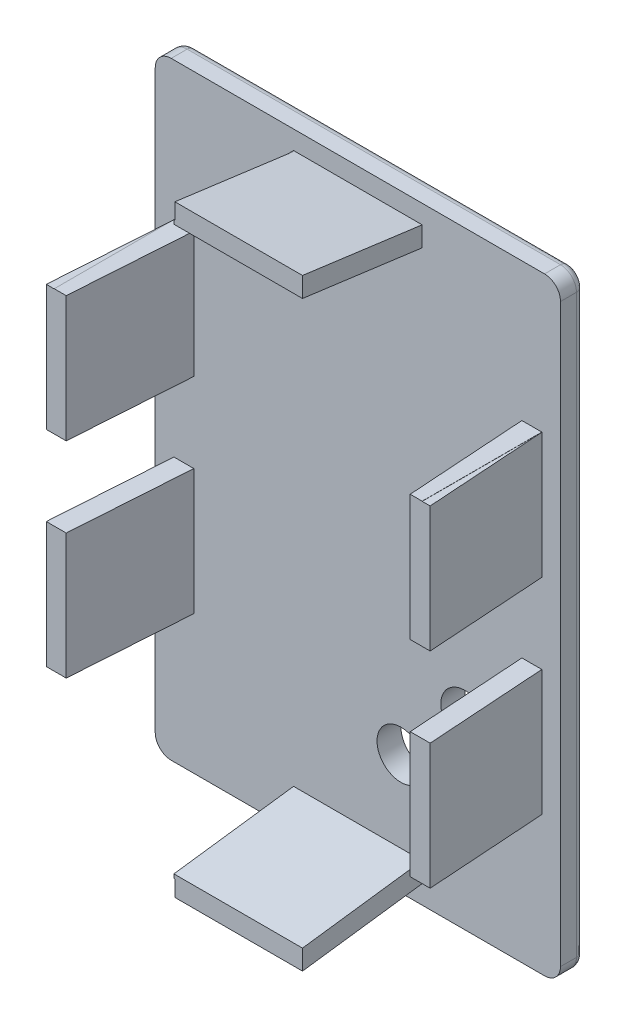
SolidWorks part; units mm, degrees
material "PLA"
ref_plane "Alzado" through (0, 0, 0) normal (0, 0, 1) x (1, 0, 0)
ref_plane "Planta" through (0, 0, 0) normal (0, 1, 0) x (1, 0, 0)
ref_plane "Vista lateral" through (0, 0, 0) normal (1, 0, 0) x (0, 0, -1)
sketch "Croquis1" plane through (0, 0, 0) normal (0, 0, 1) x (1, 0, 0)
  line L1 (25.4, 38.1) -> (-25.4, 38.1)
  line L2 (25.4, 38.1) -> (25.4, -38.1)
  line L3 (25.4, -38.1) -> (-25.4, -38.1)
  line L4 (-25.4, 38.1) -> (-25.4, -38.1)
  line L5 (25.4, 38.1) -> (-25.4, -38.1) construction
  line L6 (25.4, -38.1) -> (-25.4, 38.1) construction
  point P0 (0, 0)
  dimension "D1" = 76.2
  dimension "D2" = 50.8
extrude "Saliente-Extruir1" add sketch "Croquis1" along normal blind 18
sketch "Croquis2" plane through (0, 0, 18) normal (0, 0, 1) x (1, 0, 0)
  line L0 (25.4, 38.1) -> (-25.4, 38.1) construction
  line L1 (-23.06, 35.76) -> (23.06, 35.76)
  line L2 (-23.06, 35.76) -> (-23.06, -35.76)
  line L3 (-23.06, -35.76) -> (23.06, -35.76)
  line L4 (23.06, 35.76) -> (23.06, -35.76)
  line L5 (-25.4, -38.1) -> (25.4, -38.1) construction
  line L6 (-25.4, 38.1) -> (-25.4, -38.1) construction
  line L7 (25.4, -38.1) -> (25.4, 38.1) construction
  line L9 (-25.4, 38.1) -> (25.4, 38.1)
  line L10 (-25.4, 38.1) -> (-25.4, -38.1)
  line L11 (-25.4, -38.1) -> (25.4, -38.1)
  line L12 (25.4, 38.1) -> (25.4, -38.1)
  line L13 (-19.4, 32.1) -> (19.4, 32.1)
  line L14 (-19.4, 32.1) -> (-19.4, -32.1)
  line L15 (-19.4, -32.1) -> (19.4, -32.1)
  line L16 (19.4, 32.1) -> (19.4, -32.1)
  line M9 (-25.4, 38.1) -> (-25.4, -38.1)
  line M10 (-25.4, -38.1) -> (25.4, -38.1)
  line M11 (25.4, -38.1) -> (25.4, 38.1)
  line M12 (25.4, 38.1) -> (-25.4, 38.1)
  dimension "D1" = 2.34
  dimension "D2" = 2.34
  dimension "D3" = 2.34
  dimension "D4" = 2.34
  dimension "D5" = 6
  dimension "D6" = 6
  dimension "D7" = 6
  dimension "D8" = 6
extrude "Cortar-Extruir1" cut sketch "Croquis2" against normal blind 15 contours L1 L4 L3 L2 M12 M9 M10 M11 | L16 L13 L14 L15
sketch "Croquis3" plane through (0, 0, 18) normal (0, 0, 1) x (1, 0, 0)
  line L0 (-23.06, 35.76) -> (-23.06, -35.76) construction
  line L1 (-23.06, 22.1) -> (-19.4, 22.1)
  line L2 (-23.06, 22.1) -> (-23.06, -22.1)
  line L3 (-23.06, -22.1) -> (-19.4, -22.1)
  line L4 (-19.4, 22.1) -> (-19.4, -22.1)
  line L5 (-19.4, 32.1) -> (-19.4, -32.1) construction
  line L6 (-19.4, -32.1) -> (19.4, -32.1) construction
  line L7 (-9.4, -32.1) -> (9.3837, -32.1)
  line L8 (-9.4, -32.1) -> (-9.4, -35.76)
  line L9 (-9.4, -35.76) -> (9.3837, -35.76)
  line L10 (9.3837, -32.1) -> (9.3837, -35.76)
  line L11 (-23.06, -35.76) -> (23.06, -35.76) construction
  line L12 (19.4, 32.1) -> (19.4, -32.1) construction
  line L13 (19.4, -22.1) -> (23.06, -22.1)
  line L14 (19.4, -22.1) -> (19.4, 22.1)
  line L15 (19.4, 22.1) -> (23.06, 22.1)
  line L16 (23.06, -22.1) -> (23.06, 22.1)
  line L17 (23.06, 35.76) -> (23.06, -35.76) construction
  line L18 (-23.06, 35.76) -> (23.06, 35.76) construction
  line L19 (-9.4, 35.76) -> (9.4, 35.76)
  line L20 (-9.4, 35.76) -> (-9.4, 32.1)
  line L21 (-9.4, 32.1) -> (9.4, 32.1)
  line L22 (9.4, 35.76) -> (9.4, 32.1)
  line L23 (-19.4, 32.1) -> (19.4, 32.1) construction
  line L24 (-19.4, 32.1) -> (-19.4, -32.1) construction
  line L25 (19.4, 32.1) -> (19.4, -32.1) construction
  dimension "D1" = 10
  dimension "D2" = 10
  dimension "D3" = 10
  dimension "D4" = 10
  dimension "D5" = 10
  dimension "D6" = 10
  dimension "D7" = 10
extrude "Cortar-Extruir2" [suppressed] cut sketch "Croquis3" against normal blind 7
fillet "Redondeo1" [suppressed] radius 2
fillet "Redondeo2" [suppressed] radius 1
sketch "Croquis5" [suppressed] plane through (0, -38.1, 0) normal (0, -1, 0) x (1, 0, 0)
  line L0 (-23.4, 3) -> (23.4, 3) construction
  line L1 (-3, 3) -> (3, 3)
  line L2 (-3, 3) -> (-3, 1.5)
  line L3 (-3, 1.5) -> (3, 1.5)
  line L4 (3, 3) -> (3, 1.5)
  line L5 (0, 1) -> (0, 3) construction
  line L6 (-23.4, 1) -> (23.4, 1) construction
  dimension "D1" = 3
  dimension "D2" = 3
  dimension "D3" = 1.5
extrude "Cortar-Extruir4" [suppressed] cut sketch "Croquis5" against normal blind 6
sketch "Croquis6" plane through (0, 0, 18) normal (0, 0, 1) x (1, 0, 0)
  line L0 (-23.06, 35.76) -> (-8.06, 35.76)
  line L1 (-23.06, 35.76) -> (23.06, 35.76) construction
  line L2 (-8.06, 35.76) -> (-8.06, 32.1)
  line L3 (-19.4, 32.1) -> (19.4, 32.1) construction
  line L4 (-8.06, 32.1) -> (-19.4, 32.1)
  line L5 (-19.4, 32.1) -> (-19.4, 20.76)
  line L6 (-19.4, 32.1) -> (-19.4, -32.1) construction
  line L7 (-19.4, 20.76) -> (-23.06, 20.76)
  line L8 (-23.06, 35.76) -> (-23.06, -35.76) construction
  line L9 (-23.06, 20.76) -> (-23.06, 35.76)
  line L10 (23.06, 35.76) -> (8.06, 35.76)
  line L11 (-23.06, 35.76) -> (23.06, 35.76) construction
  line L12 (8.06, 35.76) -> (8.06, 32.1)
  line L13 (8.06, 32.1) -> (19.4, 32.1)
  line L14 (19.4, 32.1) -> (19.4, -32.1) construction
  line L15 (19.4, 32.1) -> (19.4, -32.1) construction
  line L16 (19.4, 32.1) -> (19.4, 20.76)
  line L17 (19.4, 20.76) -> (23.06, 20.76)
  line L18 (23.06, 35.76) -> (23.06, -35.76) construction
  line L19 (23.06, 20.76) -> (23.06, 35.76)
  line L20 (-23.06, -35.76) -> (-23.06, -20.76)
  line L21 (-23.06, 35.76) -> (-23.06, -35.76) construction
  line L22 (-23.06, -20.76) -> (-19.4, -20.76)
  line L23 (-19.4, 32.1) -> (-19.4, -32.1) construction
  line L24 (-19.4, -20.76) -> (-19.4, -32.1)
  line L25 (-19.4, -32.1) -> (-8.06, -32.1)
  line L26 (-19.4, -32.1) -> (19.4, -32.1) construction
  line L27 (-8.06, -32.1) -> (-8.06, -35.76)
  line L28 (-23.06, -35.76) -> (23.06, -35.76) construction
  line L29 (-8.06, -35.76) -> (-23.06, -35.76)
  line L30 (23.06, -35.76) -> (8.06, -35.76)
  line L31 (-23.06, -35.76) -> (23.06, -35.76) construction
  line L32 (8.06, -35.76) -> (8.06, -32.1)
  line L33 (-19.4, -32.1) -> (19.4, -32.1) construction
  line L34 (8.06, -32.1) -> (19.4, -32.1)
  line L35 (19.4, -32.1) -> (19.4, -20.76)
  line L36 (19.4, -20.76) -> (23.06, -20.76)
  line L37 (23.06, 35.76) -> (23.06, -35.76) construction
  line L38 (23.06, -20.76) -> (23.06, -35.76)
  dimension "D1" = 15
  dimension "D2" = 15
  dimension "D3" = 15
  dimension "D4" = 15
  dimension "D5" = 15
  dimension "D6" = 15
  dimension "D7" = 15
  dimension "D8" = 15
extrude "Cortar-Extruir8" cut sketch "Croquis6" against normal blind 15
sketch "Croquis10" plane through (0, -20.76, 0) normal (0, -1, 0) x (-1, 0, 0)
  line L0 (23.06, -18) -> (24.06, -18)
  line L1 (24.06, -18) -> (23.06, -3)
  line L2 (23.06, -3) -> (23.06, -18)
  line L3 (-23.06, -18) -> (-24.06, -18)
  line L4 (-24.06, -18) -> (-23.06, -3)
  line L5 (-23.06, -3) -> (-23.06, -18)
  dimension "D1" = 1
  dimension "D2" = 1
extrude "Saliente-Extruir3" add sketch "Croquis10" against normal blind 41.5
sketch "Croquis11" plane through (0, -20.76, 0) normal (0, -1, 0) x (1, 0, 0)
  line L0 (-19.4, 18) -> (-21.56, 18)
  line L1 (-19.4, 18) -> (-24.06, 18) construction
  line L2 (-21.56, 18) -> (-20.56, 3)
  line L3 (-19.4, 3) -> (-23.06, 3) construction
  line L4 (-20.56, 3) -> (-19.4, 3)
  line L5 (-19.4, 18) -> (-19.4, 3)
  dimension "D1" = 2.5
  dimension "D2" = 1.16
extrude "Cortar-Extruir9" cut sketch "Croquis11" against normal blind 51.5
sketch "Croquis12" plane through (0, -20.76, 0) normal (0, -1, 0) x (1, 0, 0)
  line L0 (19.4, 18) -> (19.4, 3)
  line L1 (19.4, 3) -> (20.56, 3)
  line L2 (23.06, 3) -> (19.4, 3) construction
  line L3 (20.56, 3) -> (21.56, 18)
  line L4 (24.06, 18) -> (19.4, 18) construction
  line L5 (21.56, 18) -> (19.4, 18)
  dimension "D1" = 2.5
  dimension "D2" = 1.16
extrude "Cortar-Extruir10" cut sketch "Croquis12" against normal blind 51.5
sketch "Croquis13" plane through (8.06, 0, 0) normal (1, 0, 0) x (0, 0, -1)
  line L0 (-18, -35.76) -> (-18, -37.76)
  line L1 (-18, -37.76) -> (-3, -35.76)
  line L2 (-3, -35.76) -> (-18, -35.76)
  line L3 (-18, 35.76) -> (-18, 37.76)
  line L4 (-18, 37.76) -> (-3, 35.76)
  line L5 (-3, 35.76) -> (-18, 35.76)
  dimension "D1" = 2
  dimension "D2" = 2
extrude "Saliente-Extruir4" add sketch "Croquis13" against normal blind 16
sketch "Croquis14" plane through (8.06, 0, 0) normal (1, 0, 0) x (0, 0, -1)
  line L0 (-3, -32.1) -> (-18, -32.1)
  line L1 (-18, -32.1) -> (-18, -35.26)
  line L2 (-18, -32.1) -> (-18, -37.76) construction
  line L3 (-18, -35.26) -> (-3, -33.26)
  line L4 (-3, -32.1) -> (-3, -35.76) construction
  line L5 (-3, -33.26) -> (-3, -32.1)
  line L6 (-18, 32.1) -> (-18, 35.26)
  line L7 (-18, 37.76) -> (-18, 32.1) construction
  line L8 (-18, 35.26) -> (-3, 33.26)
  line L9 (-3, 35.76) -> (-3, 32.1) construction
  line L10 (-3, 33.26) -> (-3, 32.1)
  line L11 (-3, 32.1) -> (-18, 32.1)
  dimension "D1" = 2.5
  dimension "D2" = 1.16
  dimension "D3" = 2.5
  dimension "D4" = 1.16
extrude "Cortar-Extruir11" cut sketch "Croquis14" against normal blind 16.5
fillet "Redondeo3" radius 2 4 edges at (25.4, 38.1, 1.5) (-25.4, 38.1, 1.5) (-25.4, -38.1, 1.5) (25.4, -38.1, 1.5)
fillet "Redondeo4" radius 1 8 edges at (-24.8142, 37.5142, 0) (-25.4, 0, 0) (-24.8142, -37.5142, 0) (0, -38.1, 0) (24.8142, -37.5142, 0) (25.4, 0, 0) (24.8142, 37.5142, 0) (0, 38.1, 0)
sketch "Croquis15" plane through (0, 0, 18) normal (0, 0, 1) x (1, 0, 0)
  line L0 (-24.06, -0.01) -> (24.06, -0.01) construction
  line L1 (-24.06, 20.74) -> (-24.06, -20.76) construction
  line L2 (24.06, 20.74) -> (24.06, -20.76) construction
  line L4 (-24.06, 4.99) -> (24.06, 4.99)
  line L5 (-24.06, 4.99) -> (-24.06, -5.01)
  line L6 (-24.06, -5.01) -> (24.06, -5.01)
  line L7 (24.06, 4.99) -> (24.06, -5.01)
  dimension "D1" = 5
  dimension "D2" = 5
extrude "Cortar-Extruir12" cut sketch "Croquis15" against normal blind 15
sketch "Croquis16" plane through (0, -38.1, 0) normal (0, -1, 0) x (1, 0, 0)
  line L0 (-23.4, 3) -> (23.4, 3) construction
  line L1 (-4, 3) -> (4, 3)
  line L2 (-4, 3) -> (-4, 1.5)
  line L3 (-4, 1.5) -> (4, 1.5)
  line L4 (4, 3) -> (4, 1.5)
  dimension "D1" = 1.5
  dimension "D2" = 8
  dimension "D3" = 4
extrude "Cortar-Extruir13" cut sketch "Croquis16" against normal blind 2
sketch "Croquis17" plane through (0, 0, 3) normal (0, 0, 1) x (1, 0, 0)
  line L1 (-23.4, -38.1) -> (-4, -38.1) construction
  line L2 (25.4, -36.1) -> (25.4, 36.1) construction
  line L3 (4, -38.1) -> (23.4, -38.1) construction
  circle A0 centre (13.4, -23.1) radius 3
  circle A1 centre (13.4, -15.1) radius 3
  circle A2 centre (5.4, -23.1) radius 3
  dimension "D3" = 6
  dimension "D4" = 6
  dimension "D5" = 6
  dimension "D1" = 12
  dimension "D2" = 15
  dimension "D6" = 8
  dimension "D7" = 8
  dimension "D8" = 12
  dimension "D9" = 15
extrude "Cortar-Extruir14" cut sketch "Croquis17" against normal blind 10
